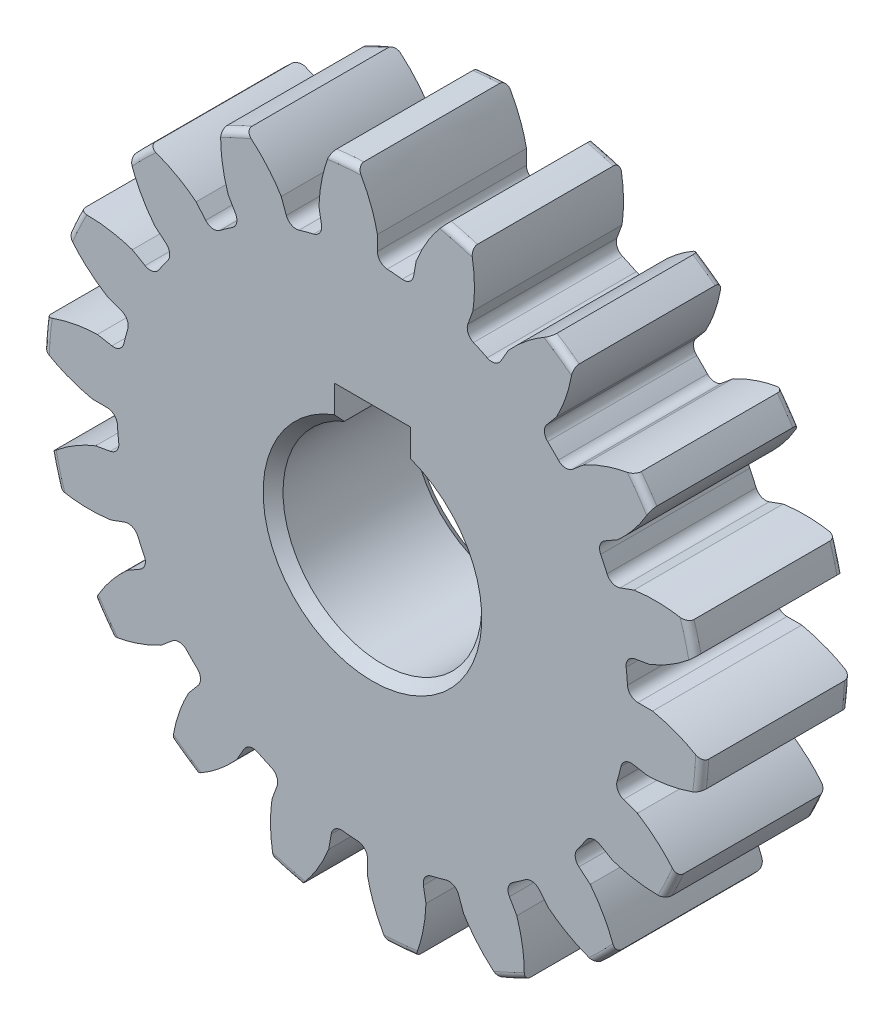
SolidWorks part; units mm, degrees
material "Plain Carbon Steel"
ref_plane "Front" through (0, 0, 0) normal (0, 0, 1) x (1, 0, 0)
ref_plane "Top" through (0, 0, 0) normal (0, 1, 0) x (1, 0, 0)
ref_plane "Right" through (0, 0, 0) normal (1, 0, 0) x (0, 0, -1)
sketch "Sketch1" plane through (0, 0, 0) normal (0, 0, 1) x (1, 0, 0)
  line L0 (-228.6, 0) -> (228.6, 0) construction
  circle A0 centre (0, 0) radius 10.541
  circle A1 centre (0, 0) radius 9.525 construction
  circle A3 centre (0, 0) radius 8.1598 construction
  dimension "D3" = 1.016
  dimension "D1" = 2.3813
extrude "Boss-Extrude1" add sketch "Sketch1" against normal blind 4.7625
sketch "Sketch2" plane through (0, 0, 0) normal (1, 0, 0) x (0, 0, -1)
  line L0 (4.7625, 0) -> (11.0998, 0)
  line L1 (4.7625, 0) -> (4.7625, 6.35)
  line L2 (4.7625, 6.35) -> (11.0998, 6.35)
  line L3 (11.0998, 6.35) -> (11.0998, 0)
  point P5 (11.0998, -6.35)
  point P6 (0, -10.541)
  point P7 (4.7625, -10.541)
  point P9 (0, 10.541)
revolve "Revolve1" add sketch "Sketch2" angle 360 mid plane about L0
fillet "Fillet2" radius 0.2108 3 edges at (10.541, 0, -4.7625) (10.541, 0, 0) (6.35, 0, -4.7625)
sketch "Sketch3" plane through (0, 0, 0) normal (0, 0, 1) x (1, 0, 0)
  line L0 (0, 0) -> (0, 10.541) construction
  line L1 (-3.0613, 8.4108) -> (0, 9.525)
  line L2 (-9.5921, 9.525) -> (9.5921, 9.525) construction
  line L3 (-9.0136, 6.2443) -> (9.0136, 12.8057) construction
  line L4 (-3.0613, 8.4108) -> (0, 0) construction
  line L5 (-7.3721, 5.0759) -> (0, 0) construction
  line L6 (-7.3721, 5.0759) -> (-2.3984, 12.2997) construction
  line L7 (-2.1265, 8.6943) -> (0, 0) construction
  line L8 (-2.1265, 8.6943) -> (0.0886, 9.2361) construction
  arc A0 (-3.0613, 8.4108) -> (-7.3721, 5.0759) centre (0, 0) ccw
  circle A1 centre (0, 0) radius 9.525 construction
  circle A2 centre (0, 0) radius 8.9506 construction
  arc A3 (-3.0613, 8.4108) -> (-2.1265, 8.6943) centre (0, 0) cw
  circle A4 centre (0, 0) radius 10.541 construction
  point P6 (0, 9.525)
  dimension "D1" = 3.2577
  dimension "Pressure Angle" = 20
  dimension "D2" = 5.5382
  dimension "D3" = 8.7705
  dimension "D4" = 0.9773
  dimension "D5" = 2.2804
sketch "Sketch4" plane through (0, 0, 0) normal (0, 0, 1) x (1, 0, 0)
  line L0 (0, 0) -> (0.827, 9.4526) construction
  line L1 (0.1576, 8.9492) -> (0.1576, 8.1582)
  line L2 (0, 9.525) -> (1.654, 9.3803) construction
  line L3 (1.3988, 8.8406) -> (1.2615, 8.0616)
  line L4 (0.1576, 8.1582) -> (0, 0) construction
  line L5 (0, 0) -> (0, 10.541) construction
  line L6 (-7.3721, 5.0759) -> (-2.3984, 12.2997) construction
  line L7 (-7.3721, 5.0759) -> (-2.3984, 12.2997) construction
  arc A0 (1.2615, 8.0616) -> (0.1576, 8.1582) centre (0, 0) ccw
  arc A1 (0, 9.525) -> (1.654, 9.3803) centre (0, 0) cw construction
  circle A2 centre (0, 0) radius 9.525 construction
  circle A3 centre (0, 0) radius 8.9506 construction
  circle A4 centre (0, 0) radius 8.1598 construction
  arc A5 (4.4978, 11.6964) -> (-2.3984, 12.2997) centre (0, 0) ccw
  spline S0 degree 2 poles (-2.3984, 12.2997) (-0.2792, 11.04) (0.1576, 8.9492) knots 0 0 0 1 1 1
  spline S1 degree 2 poles (4.4978, 11.6964) (2.1921, 10.8237) (1.3988, 8.8406) knots 0 0 0 1 1 1
  dimension "D1" = 1.6624
extrude "Cut-Extrude1" cut sketch "Sketch4" against normal through all
fillet "Fillet1" radius 0.3325 2 edges at (1.2615, 8.0616, -2.3813) (0.1576, 8.1582, -2.3813)
pattern_circular "CirPattern1" count 18 over 360 about axis through (0, 0, -4.7625) along (0, 0, 1) of "Cut-Extrude1", "Fillet1"
sketch "Sketch5" plane through (0, 0, 0) normal (0, 0, 1) x (1, 0, 0)
  line L0 (0, 4.3663) -> (0, 0) construction
  line L1 (-1.1906, 2.9433) -> (1.1906, 2.9433) construction
  line L2 (-1.1906, 2.9433) -> (-1.1906, 4.3663) construction
  line L3 (-1.1906, 4.3663) -> (1.1906, 4.3663) construction
  line L4 (1.1906, 2.9433) -> (1.1906, 4.3663) construction
  line L5 (-1.1906, 2.9433) -> (1.1906, 4.3663) construction
  line L6 (-1.1906, 4.3663) -> (1.1906, 2.9433) construction
  circle A0 centre (0, 0) radius 3.175
  point P3 (0, 3.6548)
  point P8 (0, 3.175)
  point P9 (0, -3.175)
  dimension "Bore Min" = 6.35
  dimension "Keyway Wd" = 2.3813
  dimension "Keyway Dpt." = 1.1913
extrude "Cut-Extrude2" cut sketch "Sketch5" against normal through all
sketch "Pitch Dia" plane through (0, 0, 0) normal (0, 0, 1) x (1, 0, 0)
  circle A0 centre (0, 0) radius 9.525 construction
  circle A1 centre (0, 0) radius 9.525 construction
sketch "Sketch6" plane through (0, 0, -4.7625) normal (0, 0, -1) x (-1, 0, 0)
  circle A0 centre (0, 0) radius 9.525
  dimension "D1" = 19.05
extrude "Cut-Extrude3" cut sketch "Sketch6" along normal through all
chamfer "Chamfer1" distance 0.3175 angle 45 2 edges at (3.175, 0, 0) (-3.175, 0, -4.7625)
sketch "Sketch7" plane through (0, 0, -4.7625) normal (0, 0, -1) x (-1, 0, 0)
  line L0 (0, 10.8347) -> (0, -11.529) construction
  line L1 (-1.216, 1.7169) -> (1.216, 1.7169)
  line L2 (-1.216, 1.7169) -> (-1.216, 4.1489)
  line L3 (-1.216, 4.1489) -> (1.216, 4.1489)
  line L4 (1.216, 1.7169) -> (1.216, 4.1489)
  line L5 (-14.1417, 2.9329) -> (12.5826, 2.9329) construction
  circle A2 centre (0, 0) radius 3.175 construction
  point P7 (1.216, 2.9329)
  point P11 (-1.216, 2.9329)
  dimension "D1" = 2.432
  dimension "D2" = 2.432
extrude "Cut-Extrude4" cut sketch "Sketch7" against normal through all both and the other way through all
equation "\"D1@Boss-Extrude1\" = \"Face Wd@Sketch2\""
equation "\"D1@Sketch4\" = 1.5708/(\"Number of Teeth@Sketch1\"/\"Ptich Dia@Sketch1\")"
equation "\"D1@Chamfer1\" = \"B Hub Dia@Sketch2\"*.025"
equation "\"D1@CirPattern1\" = \"Number of Teeth@Sketch1\""
equation "\"D1@Fillet1\" = \"D1@Sketch4\"*.2"
equation "\"D1@Fillet2\" = \"OD@Sketch1\"*.01"
equation "\"D1@Sketch1\" = 2.250/(\"Number of Teeth@Sketch1\"/\"Ptich Dia@Sketch1\")"
